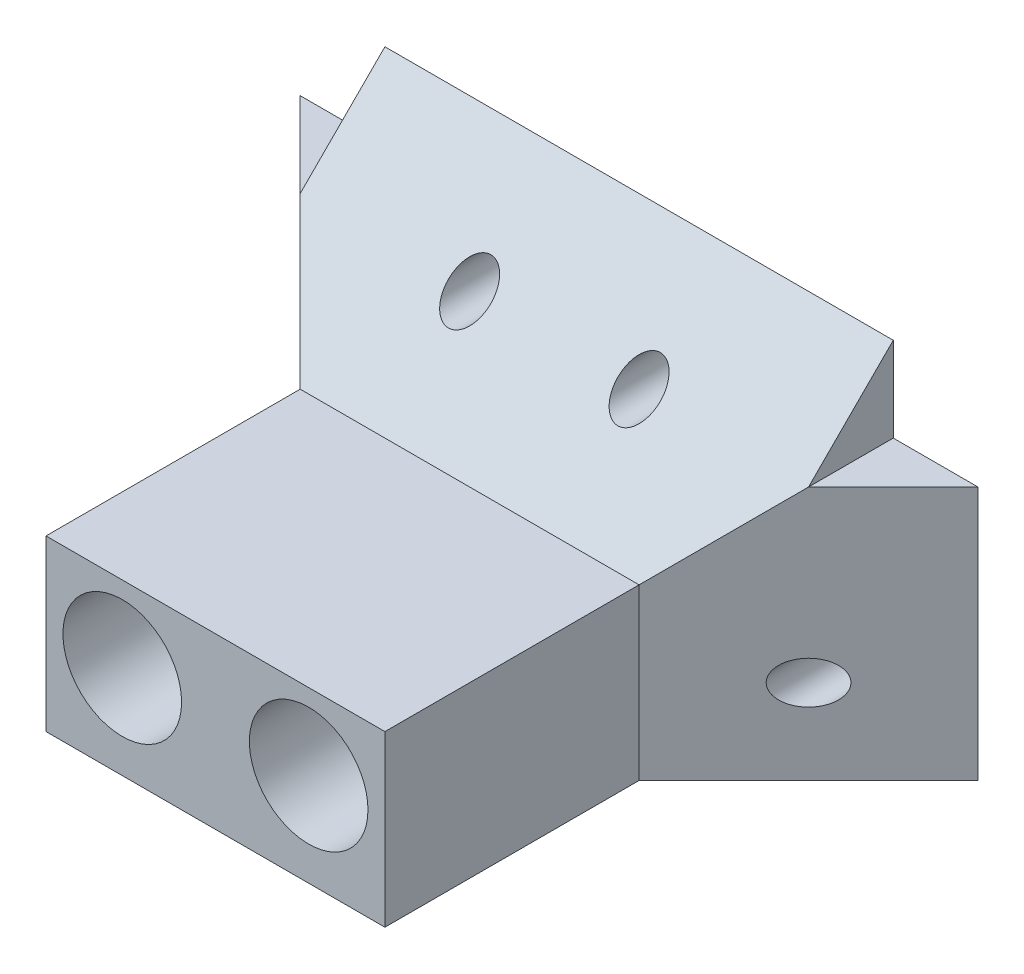
SolidWorks part; units mm, degrees
ref_plane "정면" through (0, 0, 0) normal (0, 0, 1) x (1, 0, 0)
ref_plane "윗면" through (0, 0, 0) normal (0, 1, 0) x (1, 0, 0)
ref_plane "우측면" through (0, 0, 0) normal (1, 0, 0) x (0, 0, -1)
sketch "스케치1" plane through (0, 0, 0) normal (0, 0, 1) x (1, 0, 0)
  line L1 (-10, 10) -> (10, 10)
  line L2 (-10, 10) -> (-10, -10)
  line L3 (-10, -10) -> (10, -10)
  line L4 (10, 10) -> (10, -10)
  line L5 (-10, 10) -> (10, -10) construction
  line L6 (-10, -10) -> (10, 10) construction
  point P0 (0, 0)
  dimension "D1" = 20
  dimension "D2" = 20
extrude "보스-돌출1" add sketch "스케치1" along normal blind 40
sketch "스케치2" plane through (10, 0, 0) normal (1, 0, 0) x (0, 0, -1)
  line L0 (0, -10) -> (0, 10) construction
  line L1 (-15, 7.5) -> (-5, 7.5)
  line L2 (-15, 7.5) -> (-15, -7.5)
  line L3 (-15, -7.5) -> (-5, -7.5)
  line L4 (-5, 7.5) -> (-5, -7.5)
  line L5 (-15, 7.5) -> (-5, -7.5) construction
  line L6 (-15, -7.5) -> (-5, 7.5) construction
  line L7 (-40, -10) -> (0, -10) construction
  point P0 (-10, 0)
  dimension "D1" = 10
  dimension "D2" = 10
  dimension "D3" = 15
  dimension "D4" = 10
extrude "컷-돌출1" cut sketch "스케치2" against normal blind 7.0711
sketch "스케치4" plane through (0, 0, 0) normal (0, 1, 0) x (1, 0, 0)
  line L0 (0, -30.773) -> (0, 0.8163) construction
pattern_circular "원형 패턴1" count 4 over 360 about axis through (0, 0, 0) along (0, 0, 1) of "컷-돌출1"
sketch "스케치5" plane through (0, 0, 40) normal (0, 0, 1) x (1, 0, 0)
  line L0 (-10, 10) -> (-10, -10) construction
  line L1 (-10, -10) -> (10, -10) construction
  line L2 (10, -10) -> (10, 10) construction
  line L3 (10, 10) -> (-10, 10) construction
  circle A0 centre (-5.5, 5.5) radius 3.5
  circle A1 centre (5.5, 5.5) radius 3.5
  circle A2 centre (-5.5, -5.5) radius 3.5
  circle A3 centre (5.5, -5.5) radius 3.5
  dimension "D1" = 7
  dimension "D2" = 7
  dimension "D3" = 7
  dimension "D4" = 7
  dimension "D5" = 4.5
  dimension "D6" = 4.5
  dimension "D7" = 4.5
  dimension "D8" = 4.5
  dimension "D9" = 4.5
  dimension "D10" = 4.5
  dimension "D11" = 4.5
  dimension "D12" = 4.5
extrude "컷-돌출2" cut sketch "스케치5" along a picked direction on the side against the normal blind 25
sketch "스케치6" plane through (0, 0, 0) normal (0, 0, -1) x (-1, 0, 0)
  line L5 (-14.8088, -2.95) -> (-14.8088, 2.95)
  line L7 (-14.8088, 2.95) -> (-2.95, 2.95)
  line L8 (-2.95, 2.95) -> (-2.95, 12.3603)
  line L10 (-2.95, 12.3603) -> (2.95, 12.3603)
  line L11 (2.95, 12.3603) -> (2.95, 2.95)
  line L12 (2.95, 2.95) -> (13.8521, 2.95)
  line L14 (13.8521, 2.95) -> (13.8521, -2.95)
  line L15 (13.8521, -2.95) -> (2.95, -2.95)
  line L16 (2.95, -2.95) -> (2.95, -13.9757)
  line L18 (2.95, -13.9757) -> (-2.95, -13.9757)
  line L19 (-2.95, -13.9757) -> (-2.95, -2.95)
  line L20 (-2.95, -2.95) -> (-14.8088, -2.95)
  dimension "D1" = 5.9
  dimension "D2" = 2.95
  dimension "D3" = 5.9
  dimension "D4" = 5.9
  dimension "D5" = 5.9
  dimension "D6" = 2.95
  dimension "D7" = 2.95
  dimension "D8" = 2.95
extrude "컷-돌출3" cut sketch "스케치6" against normal blind 5
sketch "스케치8" plane through (0, 0, 0) normal (0, 1, 0) x (1, 0, 0)
  line L5 (-11.0684, 1.3381) -> (11.5394, 1.3381)
  line L6 (-11.0684, 1.3381) -> (-11.0684, -40.7573)
  line L7 (-11.0684, -40.7573) -> (11.5394, -40.7573)
  line L8 (11.5394, 1.3381) -> (11.5394, -40.7573)
sketch "스케치9" plane through (0, 0, 5) normal (0, 0, -1) x (-1, 0, 0)
  line L1 (-2.9289, 2.9289) -> (2.95, 2.9289)
  line L2 (-2.9289, 2.9289) -> (-2.9289, -2.95)
  line L3 (-2.9289, -2.95) -> (2.95, -2.95)
  line L4 (2.95, 2.9289) -> (2.95, -2.95)
extrude "컷-돌출5" cut sketch "스케치9" against normal blind 5
sketch "스케치11" plane through (10, 0, 0) normal (1, 0, 0) x (0, 0, -1)
  line L1 (-15, 15) -> (-25, 15)
  line L2 (-15, 15) -> (-15, -15)
  line L3 (-15, -15) -> (-25, -15)
  line L4 (-25, 15) -> (-25, -15)
  dimension "D1" = 30
  dimension "D2" = 10
  dimension "D3" = 15
extrude "보스-돌출2" add sketch "스케치11" along normal blind 10
sketch "스케치12" plane through (0, 15, 0) normal (0, 1, 0) x (1, 0, 0)
  line L0 (20, -15) -> (10, -25)
  line L1 (10, -25) -> (20, -25)
  line L2 (20, -25) -> (20, -15)
extrude "컷-돌출6" cut sketch "스케치12" against normal blind 30
sketch "스케치14" plane through (0, 0, 0) normal (1, 0, 0) x (0, 0, -1)
  line L0 (-45.6435, 0) -> (9.8052, 0) construction
sketch "스케치13" plane through (0, 0, 15) normal (0, 0, -1) x (-1, 0, 0)
  line L0 (-10, 2.95) -> (-10, 10) construction
  line L1 (-10, -10) -> (-10, -2.95) construction
  line L4 (-20, -15) -> (-10, -15) construction
  line L5 (-20, 15) -> (-10, 15) construction
  circle A0 centre (-15, -5) radius 1.25
  circle A1 centre (-15, 5) radius 1.25
  dimension "D5" = 2.5
  dimension "D6" = 2.5
  dimension "D1" = 5
  dimension "D2" = 5
  dimension "D3" = 10
  dimension "D4" = 10
extrude "컷-돌출7" cut sketch "스케치13" against normal blind 10
pattern_circular "원형 패턴2" count 4 over 360 about axis through (0, 0, 0) along (0, 0, 1) of "컷-돌출7", "컷-돌출6", "보스-돌출2"
ref_plane "평면1" through (0, 0, 25) normal (0, 0, -1) x (-1, 0, 0)
sketch "스케치16" plane through (0, -10, 0) normal (0, -1, 0) x (1, 0, 0)
  line L0 (-2.9289, 10) -> (2.9289, 10) construction
  line L1 (10, 0) -> (-10, 0)
  line L2 (10, 0) -> (10, 10)
  line L3 (10, 10) -> (-10, 10)
  line L4 (-10, 0) -> (-10, 10)
  dimension "D1" = 0
extrude "컷-돌출11" cut sketch "스케치16" against normal blind 40
sketch "스케치17" plane through (0, 0, 10) normal (0, 0, -1) x (-1, 0, 0)
  line L1 (-10, 10) -> (10, 10)
  line L2 (-10, 10) -> (-10, -10)
  line L3 (-10, -10) -> (10, -10)
  line L4 (10, 10) -> (10, -10)
  line L5 (-10, 10) -> (10, -10) construction
  line L6 (-10, -10) -> (10, 10) construction
  line L7 (-2.9289, 2.9289) -> (2.9289, 2.9289)
  line L8 (-2.9289, 2.9289) -> (-2.9289, -2.9289)
  line L9 (-2.9289, -2.9289) -> (2.9289, -2.9289)
  line L10 (2.9289, 2.9289) -> (2.9289, -2.9289)
  line L11 (-2.9289, 2.9289) -> (2.9289, -2.9289) construction
  line L12 (-2.9289, -2.9289) -> (2.9289, 2.9289) construction
  point P0 (0, 0)
  point P7 (0, 0)
extrude "컷-돌출12" cut sketch "스케치17" against normal blind 5
sketch "스케치18" plane through (0, 10, 0) normal (0, -1, 0) x (1, 0, 0)
  line L0 (10, 25) -> (15, 25)
  line L1 (15, 25) -> (15, 20)
  line L2 (15, 20) -> (10, 25)
extrude "컷-돌출13" cut sketch "스케치18" against normal blind 10 and the other way through all
sketch "스케치19" plane through (0, 0, 0) normal (0, 1, 0) x (1, 0, 0)
  line L1 (-31.1319, 8.0592) -> (50.4041, 8.0592)
  line L2 (-31.1319, 8.0592) -> (-31.1319, -60.7276)
  line L3 (-31.1319, -60.7276) -> (50.4041, -60.7276)
  line L4 (50.4041, 8.0592) -> (50.4041, -60.7276)
extrude "컷-돌출16" cut sketch "스케치19" against normal blind 400 contours L1 L4 L3 L2
sketch "스케치20" plane through (0, 0, 0) normal (1, 0, 0) x (0, 0, -1)
  line L1 (-53.3755, 28.6467) -> (19.7058, 28.6467)
  line L2 (-53.3755, 28.6467) -> (-53.3755, -15.7116)
  line L3 (-53.3755, -15.7116) -> (19.7058, -15.7116)
  line L4 (19.7058, 28.6467) -> (19.7058, -15.7116)
